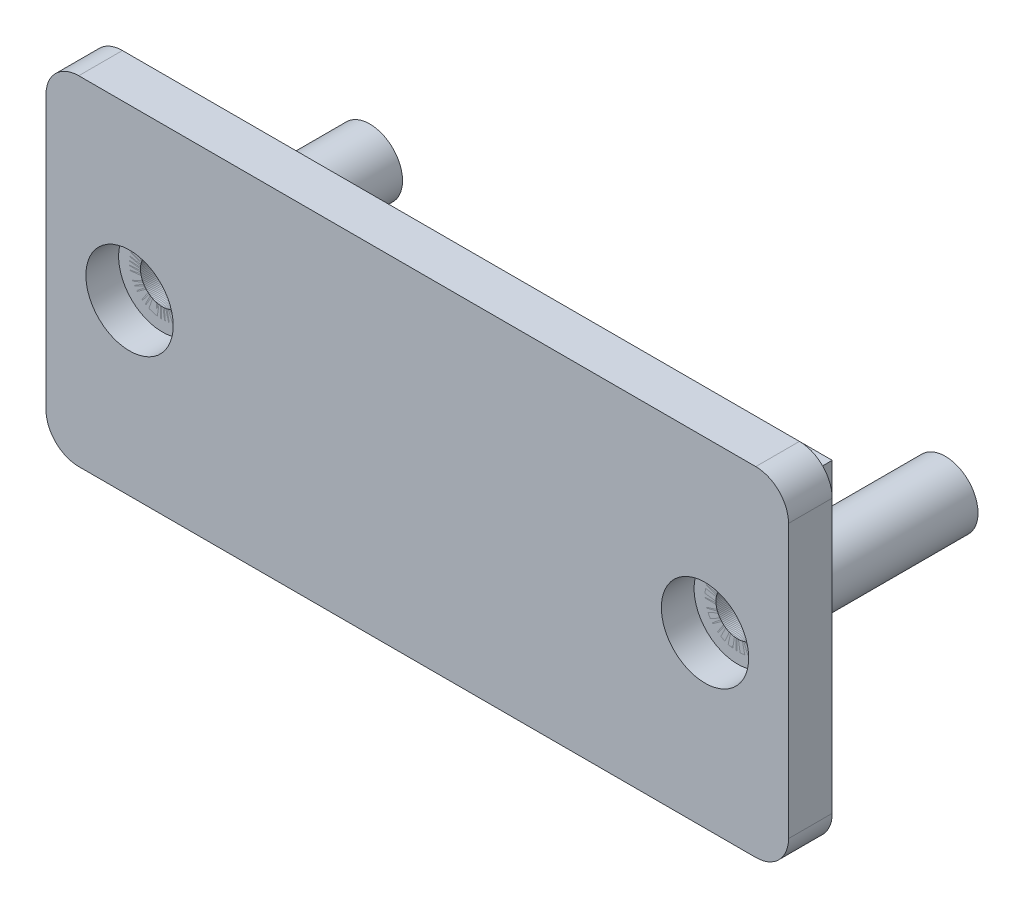
SolidWorks part; units mm, degrees
ref_plane "Alzado" through (0, 0, 0) normal (0, 0, 1) x (1, 0, 0)
ref_plane "Planta" through (0, 0, 0) normal (0, 1, 0) x (1, 0, 0)
ref_plane "Vista lateral" through (0, 0, 0) normal (1, 0, 0) x (0, 0, -1)
sketch "Croquis3" plane through (0, 0, 0) normal (0, 0, 1) x (1, 0, 0)
  circle A0 centre (26.35, 0) radius 2
  circle A1 centre (26.35, 0) radius 3
  circle A2 centre (-26.35, 0) radius 2
  circle A3 centre (-26.35, 0) radius 3
extrude "Saliente-Extruir2" add sketch "Croquis3" against normal blind 22
sketch "Croquis4" plane through (0, 0, 0) normal (0, 0, 1) x (1, 0, 0)
  line L0 (-31, 15.5) -> (31, 15.5)
  line L1 (-31, -15.5) -> (31, -15.5)
  line L2 (34, 12.5) -> (34, -12.5)
  line L3 (-31, 12.5) -> (-31, -12.5)
  line L5 (-31, -12.5) -> (31, -12.5)
  line L6 (-31, 12.5) -> (31, 12.5)
  line L7 (31, 12.5) -> (31, -12.5)
  line L8 (-34, 12.5) -> (-34, -12.5)
  arc A0 (-34, -12.5) -> (-31, -15.5) centre (-31, -12.5) ccw
  arc A1 (31, -15.5) -> (34, -12.5) centre (31, -12.5) ccw
  arc A2 (34, 12.5) -> (31, 15.5) centre (31, 12.5) ccw
  arc A3 (-34, 12.5) -> (-31, 15.5) centre (-31, 12.5) cw
extrude "Saliente-Extruir3" add sketch "Croquis4" against normal blind 4 separate body
ref_plane "Plano1" through (0, 16, 0) normal (0, 1, 0) x (1, 0, 0)
sketch "Croquis6" plane through (0, 0, 0) normal (0, 0, 1) x (1, 0, 0)
  line L0 (31, -12.5) -> (31, 12.5) construction
  line L1 (-31, 12.5) -> (31, 12.5)
  line L2 (-31, 12.5) -> (-31, -12.5)
  line L3 (-31, -12.5) -> (31, -12.5)
  line L4 (31, 12.5) -> (31, -12.5)
extrude "Saliente-Extruir4" add sketch "Croquis6" against normal blind 8
sketch "Croquis7" plane through (0, 0, 0) normal (0, 0, 1) x (1, 0, 0)
  circle A0 centre (-26.35, 0) radius 2
  circle A1 centre (26.35, 0) radius 2
extrude "Cortar-Extruir1" cut sketch "Croquis7" against normal blind 29 and the other way blind 26
ref_plane "Plano2" through (0, 0, -4) normal (0, 0, 1) x (1, 0, 0)
sketch "Croquis9" plane through (0, 0, -4) normal (0, 0, 1) x (1, 0, 0)
  line L1 (-31, -12.5) -> (-30, -12.5)
  line L2 (-31, -12.5) -> (-31, -11.5)
  line L3 (-8, 11.5) -> (-8, -4.5)
  line L4 (-8, -4.5) -> (8, -4.5)
  line L5 (31, 12.5) -> (30, 12.5)
  line L6 (31, 12.5) -> (31, 11.5)
  line L7 (8, -4.5) -> (8, 11.5)
  line L8 (8, 11.5) -> (30, 11.5)
  line L9 (-30, -11.5) -> (30, -11.5)
  line L10 (-30, -11.5) -> (-30, 11.5)
  line L11 (-30, 11.5) -> (-8, 11.5)
  line L12 (30, -11.5) -> (30, 11.5)
  line L13 (31, 12.5) -> (-31, 12.5)
  line L14 (31, 12.5) -> (31, -12.5)
  line L15 (31, -12.5) -> (-31, -12.5)
  line L16 (-31, 12.5) -> (-31, -12.5)
extrude "Cortar-Extruir2" cut sketch "Croquis9" against normal blind 4 contours L13 L16 L2 L1 L15 L14 L6 L5 L12 L9 L10 L11 | L9 L12 L11 L10
sketch "Croquis10" plane through (0, 0, 0) normal (0, 0, 1) x (1, 0, 0)
  circle A0 centre (-26.35, 0) radius 2
  circle A1 centre (-26.35, 0) radius 4
  circle A2 centre (26.35, 0) radius 2
  circle A3 centre (26.35, 0) radius 4
extrude "Cortar-Extruir3" cut sketch "Croquis10" against normal blind 3
